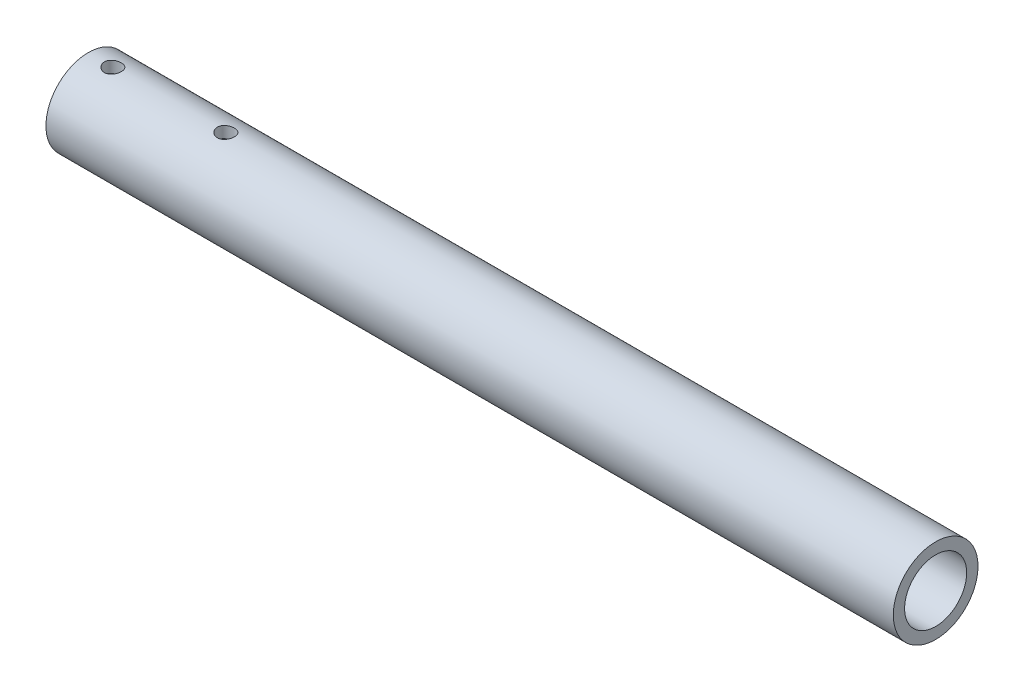
SolidWorks part; units mm, degrees
material "Thornel Mat VMA"
ref_plane "前视基准面" through (0, 0, 0) normal (0, 0, 1) x (1, 0, 0)
ref_plane "上视基准面" through (0, 0, 0) normal (0, 1, 0) x (1, 0, 0)
ref_plane "右视基准面" through (0, 0, 0) normal (1, 0, 0) x (0, 0, -1)
other "Configuration Table"
sketch "草图1" plane through (0, 0, 0) normal (1, 0, 0) x (0, 0, -1)
  circle A0 centre (0, 0) radius 7.4985
  circle A1 centre (0, 0) radius 5.4963
extrude "凸台-拉伸1" add sketch "草图1" along normal blind 150
sketch "草图2" plane through (0, 0, 0) normal (0, 1, 0) x (1, 0, 0)
  line L1 (-8.2484, 0) -> (8.2484, 0) construction
  circle A0 centre (4.36, 0) radius 1.5
  circle A1 centre (24.36, 0) radius 1.5
extrude "切除-拉伸1" cut sketch "草图2" against normal mid plane 28
